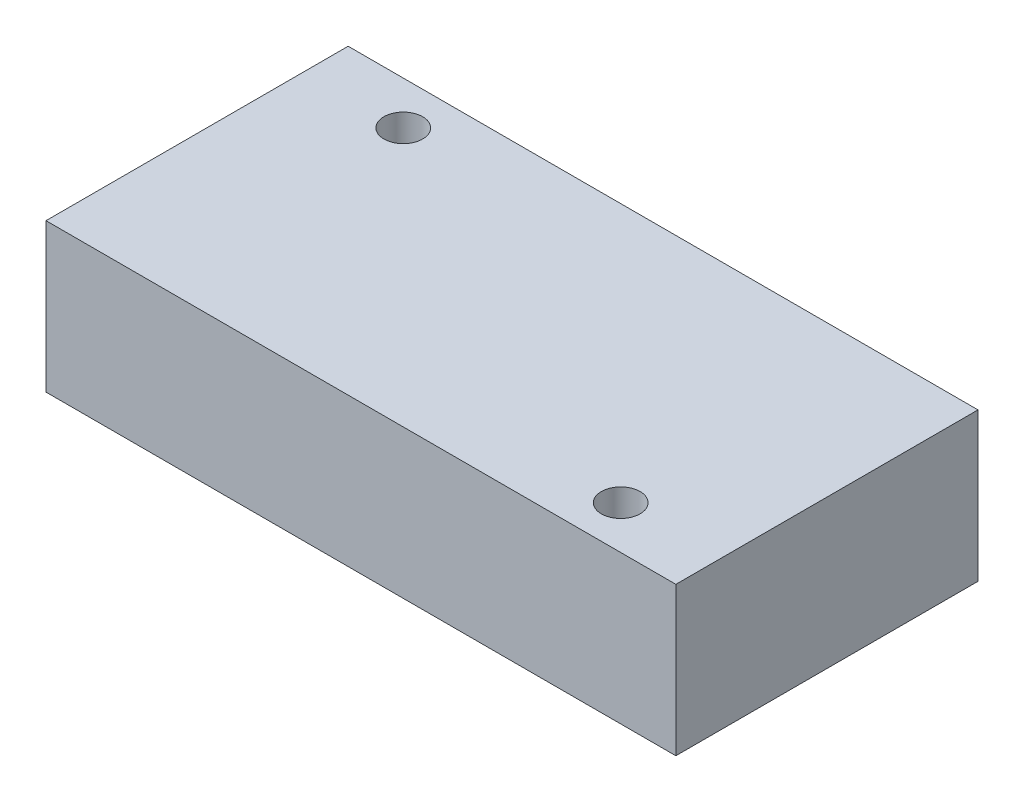
SolidWorks part; units mm, degrees
ref_plane "Front Plane" through (0, 0, 0) normal (0, 0, 1) x (1, 0, 0)
ref_plane "Top Plane" through (0, 0, 0) normal (0, 1, 0) x (1, 0, 0)
ref_plane "Right Plane" through (0, 0, 0) normal (1, 0, 0) x (0, 0, -1)
sketch "Sketch1" plane through (0, 0, 0) normal (0, 1, 0) x (1, 0, 0)
  line L1 (24.39, -11.7) -> (-24.39, -11.7)
  line L2 (24.39, -11.7) -> (24.39, 11.7)
  line L3 (24.39, 11.7) -> (-24.39, 11.7)
  line L4 (-24.39, -11.7) -> (-24.39, 11.7)
  line L5 (24.39, -11.7) -> (-24.39, 11.7) construction
  line L6 (24.39, 11.7) -> (-24.39, -11.7) construction
  point P0 (0, 0)
  dimension "D1" = 23.4
  dimension "D2" = 48.78
extrude "Boss-Extrude1" add sketch "Sketch1" along normal blind 11.5
sketch "Sketch2" plane through (0, 11.5, 0) normal (0, 1, 0) x (1, 0, 0)
  line L0 (24.39, -11.7) -> (24.39, 11.7) construction
  line L1 (-24.39, 11.7) -> (-24.39, -11.7) construction
  line L2 (-24.39, -11.7) -> (24.39, -11.7) construction
  line L3 (24.39, 11.7) -> (-24.39, 11.7) construction
  circle A0 centre (-16.78, 8.36) radius 1.5
  circle A1 centre (16.78, -8.36) radius 1.5
  dimension "D1" = 3
  dimension "D2" = 3
  dimension "D3" = 7.61
  dimension "D4" = 7.61
  dimension "D5" = 3.34
  dimension "D6" = 3.34
extrude "Cut-Extrude1" cut sketch "Sketch2" against normal up to next
